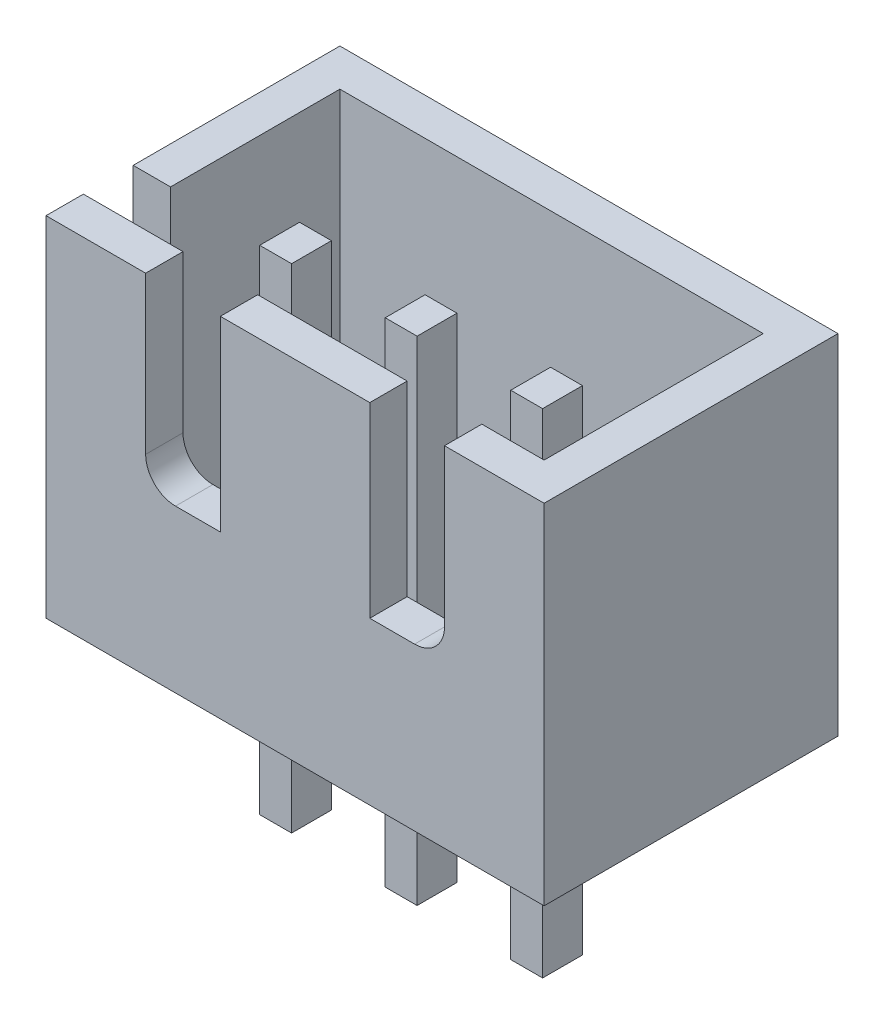
SolidWorks part; units mm, degrees
ref_plane "Alzado" through (0, 0, 0) normal (0, 0, 1) x (1, 0, 0)
ref_plane "Planta" through (0, 0, 0) normal (0, 1, 0) x (1, 0, 0)
ref_plane "Vista lateral" through (0, 0, 0) normal (1, 0, 0) x (0, 0, -1)
sketch "Croquis1" plane through (0, 0, 0) normal (0, 1, 0) x (1, 0, 0)
  line L0 (-2.48, 3.37) -> (7.52, 3.37)
  line L1 (7.52, 3.37) -> (7.52, -2.53)
  line L2 (7.52, -2.53) -> (-2.48, -2.53)
  line L3 (-2.48, -2.53) -> (-2.48, 3.37)
  line L4 (2.52, -2.53) -> (2.52, 2.1284) construction
  line L5 (-0.32, -0.4) -> (0.32, -0.4)
  line L6 (-0.32, -0.4) -> (-0.32, 0.4)
  line L7 (-0.32, 0.4) -> (0.32, 0.4)
  line L8 (0.32, -0.4) -> (0.32, 0.4)
  line L9 (-0.32, -0.4) -> (0.32, 0.4) construction
  line L10 (-0.32, 0.4) -> (0.32, -0.4) construction
  line L11 (5.36, -0.4) -> (5.36, 0.4)
  line L12 (5.36, -0.4) -> (4.72, -0.4)
  line L13 (4.72, -0.4) -> (4.72, 0.4)
  line L14 (5.36, 0.4) -> (4.72, 0.4)
  line L16 (2.2, -0.4) -> (2.84, -0.4)
  line L17 (2.2, -0.4) -> (2.2, 0.4)
  line L18 (2.2, 0.4) -> (2.84, 0.4)
  line L19 (2.84, -0.4) -> (2.84, 0.4)
  line L20 (2.2, -0.4) -> (2.84, 0.4) construction
  line L21 (2.2, 0.4) -> (2.84, -0.4) construction
  point P5 (0, 0)
  point P16 (2.52, 0)
  dimension "D1" = 10
  dimension "D2" = 5.9
  dimension "D3" = 3.37
  dimension "D4" = 2.48
  dimension "D5" = 0.8
  dimension "D6" = 0.64
extrude "Saliente-Extruir1" add sketch "Croquis1" along normal blind 1
sketch "Croquis2" plane through (0, 1, 0) normal (0, 1, 0) x (1, 0, 0)
  line L1 (-1.73, -1.78) -> (6.77, -1.78)
  line L2 (-1.73, -1.78) -> (-1.73, 2.62)
  line L3 (-1.73, 2.62) -> (6.77, 2.62)
  line L4 (-2.48, 3.37) -> (-2.48, -2.53)
  line L5 (-2.48, -2.53) -> (7.52, -2.53)
  line L6 (7.52, -2.53) -> (7.52, 3.37)
  line L7 (7.52, 3.37) -> (-2.48, 3.37)
  line L8 (-2.48, 3.37) -> (-2.48, -2.53)
  line L9 (-2.48, -2.53) -> (7.52, -2.53)
  line L10 (7.52, -2.53) -> (7.52, 3.37)
  line L11 (7.52, 3.37) -> (-2.48, 3.37)
  line L12 (6.77, -1.78) -> (6.77, 2.62)
  line L13 (-1.73, -1.78) -> (6.77, 2.62) construction
  line L14 (-1.73, 2.62) -> (6.77, -1.78) construction
  point P2 (2.52, 0.42)
  dimension "D2" = 0.75
  dimension "D3" = 0.75
  dimension "D4" = 0.75
  dimension "D5" = 0.75
  dimension "D1" = 0
extrude "Saliente-Extruir2" add sketch "Croquis2" along normal blind 6
sketch "Croquis3" plane through (-2.48, 0, 0) normal (-1, 0, 0) x (0, 0, 1)
  line L0 (1.78, 7) -> (1.78, 4.35)
  line L1 (-3.37, 7) -> (2.53, 7) construction
  line L2 (0.78, 3.75) -> (0.78, 7)
  line L3 (2.53, 7) -> (2.53, 0) construction
  line L4 (1.18, 3.75) -> (0.78, 3.75)
  line L5 (0.78, 7) -> (1.78, 7)
  arc A1 (1.18, 3.75) -> (1.78, 4.35) centre (1.18, 4.35) ccw
  dimension "D4" = 0.6
  dimension "D1" = 0.75
  dimension "D2" = 1
  dimension "D3" = 3.25
extrude "Cortar-Extruir1" cut sketch "Croquis3" against normal blind 9
sketch "Croquis4" plane through (0, 0, 2.53) normal (0, 0, 1) x (1, 0, 0)
  line L0 (-0.48, 3.85) -> (-0.48, 7)
  line L1 (-2.48, 7) -> (7.52, 7) construction
  line L3 (5.52, 3.85) -> (5.52, 7)
  line L4 (7.52, 7) -> (7.52, 0) construction
  line L5 (2.52, 0) -> (2.52, 7) construction
  line L6 (-2.48, 0) -> (7.52, 0) construction
  line L7 (-0.48, 7) -> (5.52, 7)
  line L8 (4.02, 3.25) -> (4.02, 7)
  line L9 (4.02, 3.25) -> (4.92, 3.25)
  line L10 (1.02, 3.25) -> (1.02, 7)
  line L11 (1.02, 3.25) -> (0.12, 3.25)
  arc A0 (4.92, 3.25) -> (5.52, 3.85) centre (4.92, 3.85) ccw
  arc A1 (0.12, 3.25) -> (-0.48, 3.85) centre (0.12, 3.85) cw
  point P18 (2.52, 3.25)
  point P21 (0, 0)
  point P22 (0, 0)
  line M11 (7.52, 7) -> (-2.48, 7)
  dimension "D2" = 0.6
  dimension "D1" = 2
  dimension "D3" = 3.75
  dimension "D4" = 1.5
extrude "Cortar-Extruir2" cut sketch "Croquis4" against normal blind 2 contours A1 L11 L10 L0 M11 | L9 A0 L3 L8 M11
sketch "Croquis5" plane through (0, 0, 0) normal (0, 1, 0) x (1, 0, 0)
  line L0 (5.36, -0.4) -> (5.36, 0.4) construction
  line L1 (4.72, -0.4) -> (5.36, -0.4) construction
  line L2 (4.72, 0.4) -> (4.72, -0.4) construction
  line L3 (5.36, 0.4) -> (4.72, 0.4) construction
  line L4 (0.32, 0.4) -> (-0.32, 0.4) construction
  line L5 (0.32, -0.4) -> (0.32, 0.4) construction
  line L6 (-0.32, -0.4) -> (0.32, -0.4) construction
  line L7 (-0.32, 0.4) -> (-0.32, -0.4) construction
  line L8 (5.36, -0.4) -> (5.36, 0.4)
  line L9 (4.72, -0.4) -> (5.36, -0.4)
  line L10 (4.72, 0.4) -> (4.72, -0.4)
  line L11 (5.36, 0.4) -> (4.72, 0.4)
  line L12 (0.32, 0.4) -> (-0.32, 0.4)
  line L13 (0.32, -0.4) -> (0.32, 0.4)
  line L14 (-0.32, -0.4) -> (0.32, -0.4)
  line L15 (-0.32, 0.4) -> (-0.32, -0.4)
  line L16 (2.84, -0.4) -> (2.84, 0.4) construction
  line L17 (2.2, -0.4) -> (2.84, -0.4) construction
  line L18 (2.2, 0.4) -> (2.2, -0.4) construction
  line L19 (2.84, 0.4) -> (2.2, 0.4) construction
  line L20 (2.84, -0.4) -> (2.84, 0.4)
  line L21 (2.2, -0.4) -> (2.84, -0.4)
  line L22 (2.2, 0.4) -> (2.2, -0.4)
  line L23 (2.84, 0.4) -> (2.2, 0.4)
extrude "Saliente-Extruir3" add sketch "Croquis5" along normal blind 6.5 and the other way blind 3.4
